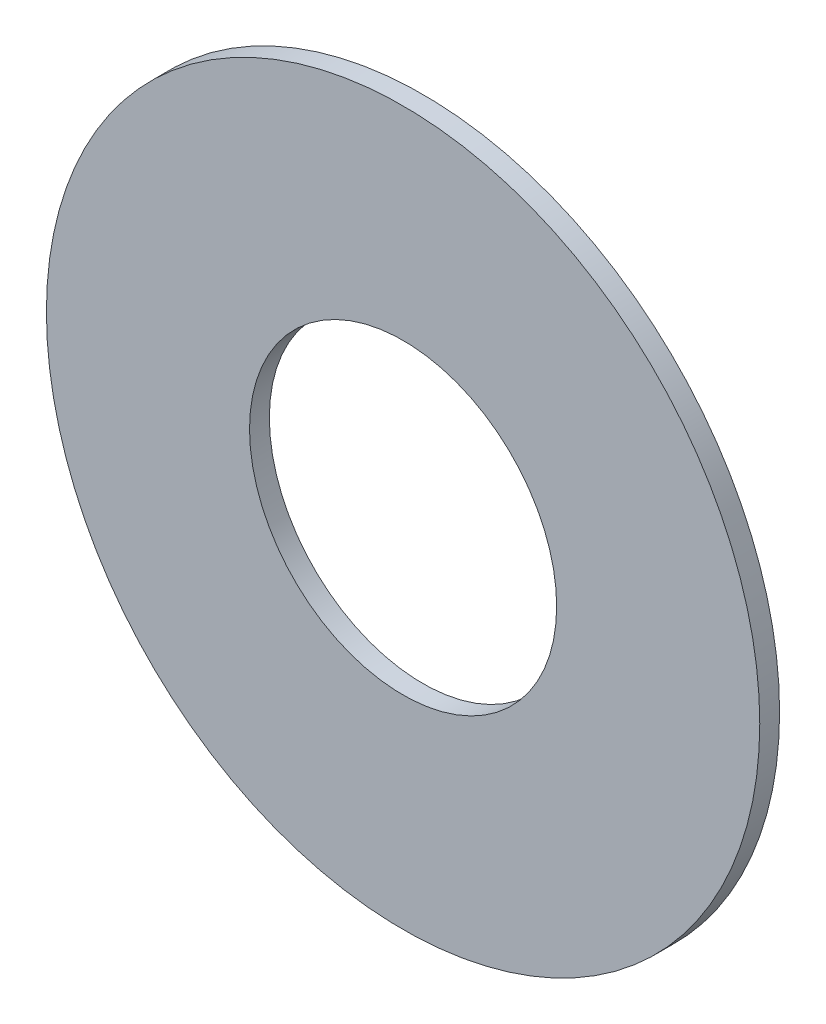
SolidWorks part; units mm, degrees
ref_plane "Front Plane" through (0, 0, 0) normal (0, 0, 1) x (1, 0, 0)
ref_plane "Top Plane" through (0, 0, 0) normal (0, 1, 0) x (1, 0, 0)
ref_plane "Right Plane" through (0, 0, 0) normal (1, 0, 0) x (0, 0, -1)
sketch "Sketch1" plane through (0, 0, 0) normal (0, 0, 1) x (1, 0, 0)
  circle A0 centre (-0.7072, 0) radius 15.5
  circle A1 centre (-0.7072, 0) radius 36
  dimension "D1" = 31
  dimension "D2" = 72
extrude "Boss-Extrude1" add sketch "Sketch1" along normal blind 2
